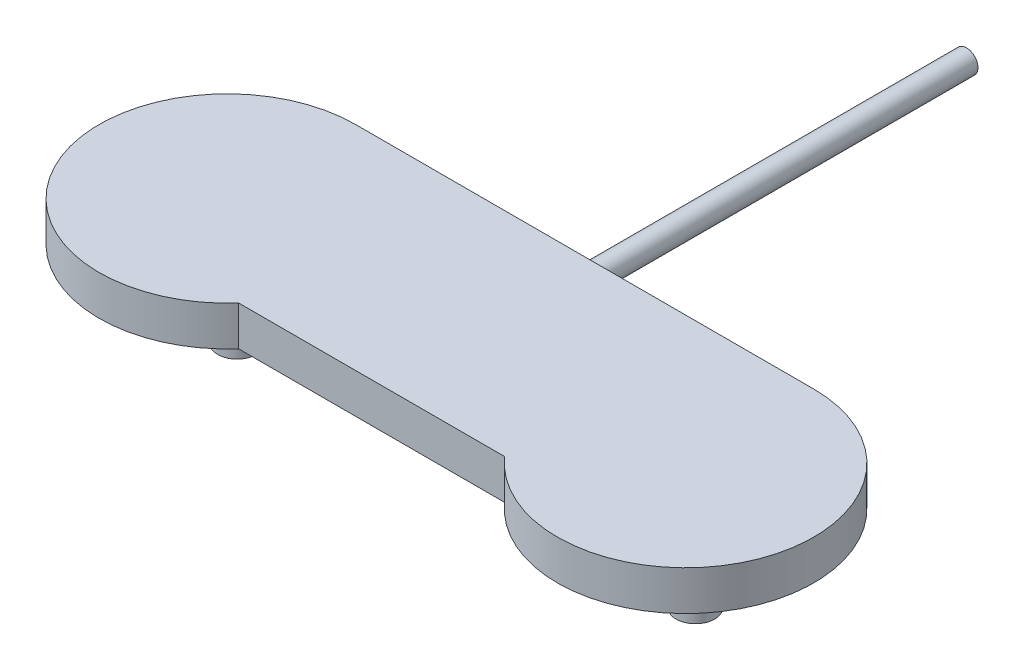
SolidWorks part; units mm, degrees
ref_plane "Front Plane" through (0, 0, 0) normal (0, 0, 1) x (1, 0, 0)
ref_plane "Top Plane" through (0, 0, 0) normal (0, 1, 0) x (1, 0, 0)
ref_plane "Right Plane" through (0, 0, 0) normal (1, 0, 0) x (0, 0, -1)
sketch "Sketch1" plane through (0, 0, 0) normal (0, 1, 0) x (1, 0, 0)
  line L0 (0, 16.153) -> (57.7366, 16.153)
  line L1 (12.1146, -10.6844) -> (45.622, -10.6844)
  arc A0 (0, 16.153) -> (12.1146, -10.6844) centre (0, 0) ccw
  arc A1 (45.622, -10.6844) -> (57.7366, 16.153) centre (57.7366, 0) ccw
extrude "Boss-Extrude1" add sketch "Sketch1" along normal blind 5
sketch "Sketch2" plane through (0, 0, 0) normal (0, 1, 0) x (1, 0, 0)
  line L0 (-5.9698, 7.1815) -> (-5.9698, -10.4851) construction
  line L1 (8.4146, -7.1815) -> (-8.4146, -7.1815) construction
  line L2 (8.4146, -7.1815) -> (8.4146, 7.1815) construction
  line L3 (8.4146, 7.1815) -> (-8.4146, 7.1815) construction
  line L4 (-8.4146, -7.1815) -> (-8.4146, 7.1815) construction
  line L5 (8.4146, -7.1815) -> (-8.4146, 7.1815) construction
  line L6 (8.4146, 7.1815) -> (-8.4146, -7.1815) construction
  line L7 (-8.4146, 4.7368) -> (13.4955, 4.7368) construction
  line L8 (10.8593, 7.1815) -> (10.8593, -9.874) construction
  line L9 (28.8683, -10.6844) -> (28.8683, 19.4054) construction
  line L10 (12.1146, -10.6844) -> (45.622, -10.6844) construction
  circle A0 centre (-8.4146, 7.1815) radius 2.4448
  circle A1 centre (-8.4146, -7.1815) radius 2.4448
  circle A2 centre (8.4146, 7.1815) radius 2.4448
  circle A3 centre (8.4146, -7.1815) radius 2.4448
  circle A4 centre (66.1511, 7.1815) radius 2.4448
  circle A5 centre (66.1511, -7.1815) radius 2.4448
  circle A6 centre (49.322, -7.1815) radius 2.4448
  circle A7 centre (49.322, 7.1815) radius 2.4448
  point P0 (0, 0)
extrude "Boss-Extrude2" add sketch "Sketch2" against normal blind 3 from offset 0
sketch "Sketch4" plane through (0, 0, -16.153) normal (0, 0, -1) x (-1, 0, 0)
  line L0 (-28.9702, 0) -> (-28.9702, 16.2562) construction
  line L1 (23.0868, 0) -> (-23.0868, 0) construction
  circle A0 centre (-28.9702, 2.4007) radius 1.4478
extrude "Boss-Extrude3" add sketch "Sketch4" along normal blind 48
